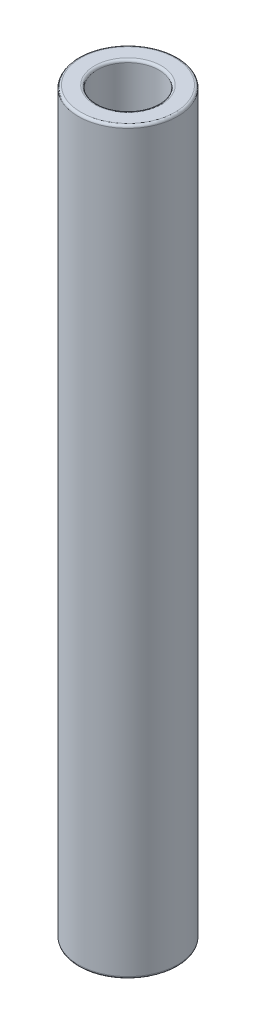
SolidWorks part; units mm, degrees
material "6061 Alloy"
ref_plane "Front Plane" through (0, 0, 0) normal (0, 0, 1) x (1, 0, 0)
ref_plane "Top Plane" through (0, 0, 0) normal (0, 1, 0) x (1, 0, 0)
ref_plane "Right Plane" through (0, 0, 0) normal (1, 0, 0) x (0, 0, -1)
sketch "Sketch1" plane through (0, 0, 0) normal (0, 1, 0) x (1, 0, 0)
  circle A0 centre (0, 0) radius 4
  circle A1 centre (0, 0) radius 2.5
  dimension "D1" = 5
  dimension "D2" = 8
extrude "Boss-Extrude1" add sketch "Sketch1" along normal blind 59.69
fillet "Fillet1" radius 0.2 4 edges at (0, 0, 2.5) (0, 0, 4) (0, 59.69, 4) (0, 59.69, 2.5)
